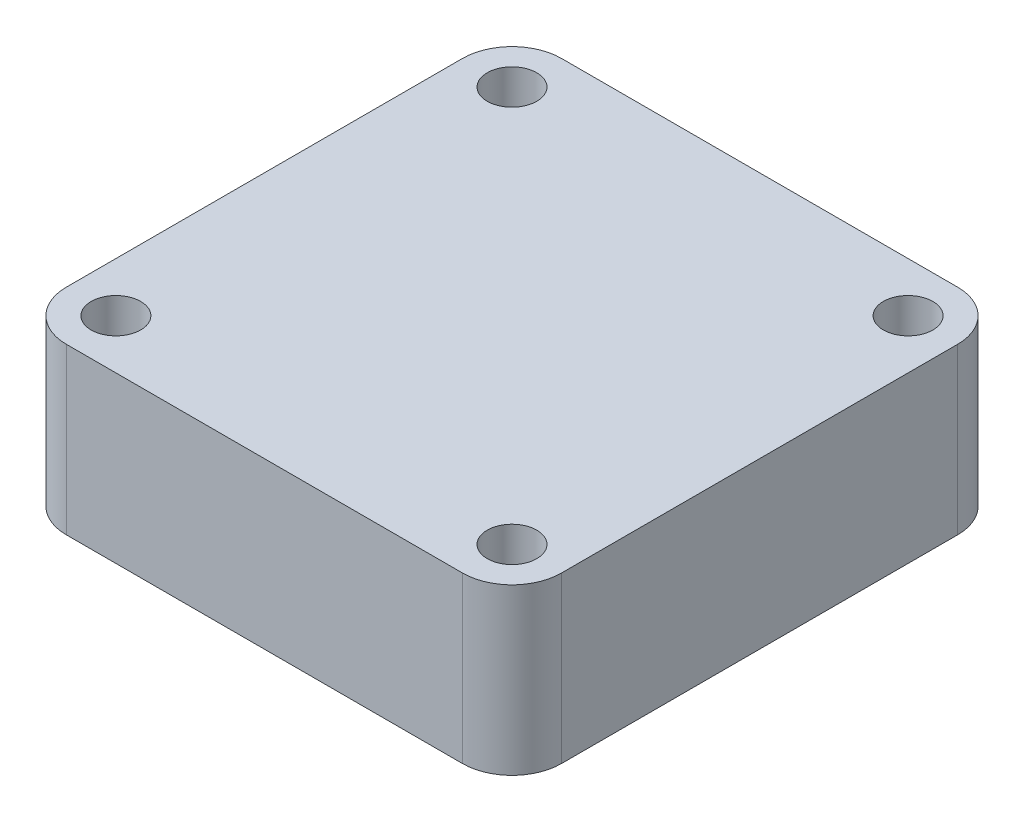
SolidWorks part; units mm, degrees
material "AISI 1035 Steel (SS)"
ref_plane "Front Plane" through (0, 0, 0) normal (0, 0, 1) x (1, 0, 0)
ref_plane "Top Plane" through (0, 0, 0) normal (0, 1, 0) x (1, 0, 0)
ref_plane "Right Plane" through (0, 0, 0) normal (1, 0, 0) x (0, 0, -1)
sketch "Sketch1" plane through (0, 0, 0) normal (0, 1, 0) x (1, 0, 0)
  line L1 (0, 0) -> (30, 0)
  line L2 (0, 0) -> (0, -30)
  line L3 (0, -30) -> (30, -30)
  line L4 (30, 0) -> (30, -30)
  dimension "D1" = 30
  dimension "D2" = 30
extrude "Boss-Extrude1" add sketch "Sketch1" along normal blind 10
sketch "Sketch2" plane through (0, 10, 0) normal (0, 1, 0) x (1, 0, 0)
  line L0 (0, 0) -> (0, -30) construction
  line L1 (30, 0) -> (0, 0) construction
  circle A0 centre (3, -3) radius 1.5
  circle A1 centre (27, -3) radius 1.5
  circle A2 centre (27, -27) radius 1.5
  circle A3 centre (3, -27) radius 1.5
  dimension "D1" = 3
  dimension "D2" = 3
  dimension "D3" = 3
  dimension "D4" = 2
  dimension "D5" = 2
extrude "Cut-Extrude1" cut sketch "Sketch2" against normal blind 10
fillet "Fillet1" radius 3 4 edges at (30, 5, 0) (30, 5, 30) (0, 5, 0) (0, 5, 30)
equation "\"D2@Sketch2\"=15-12"
